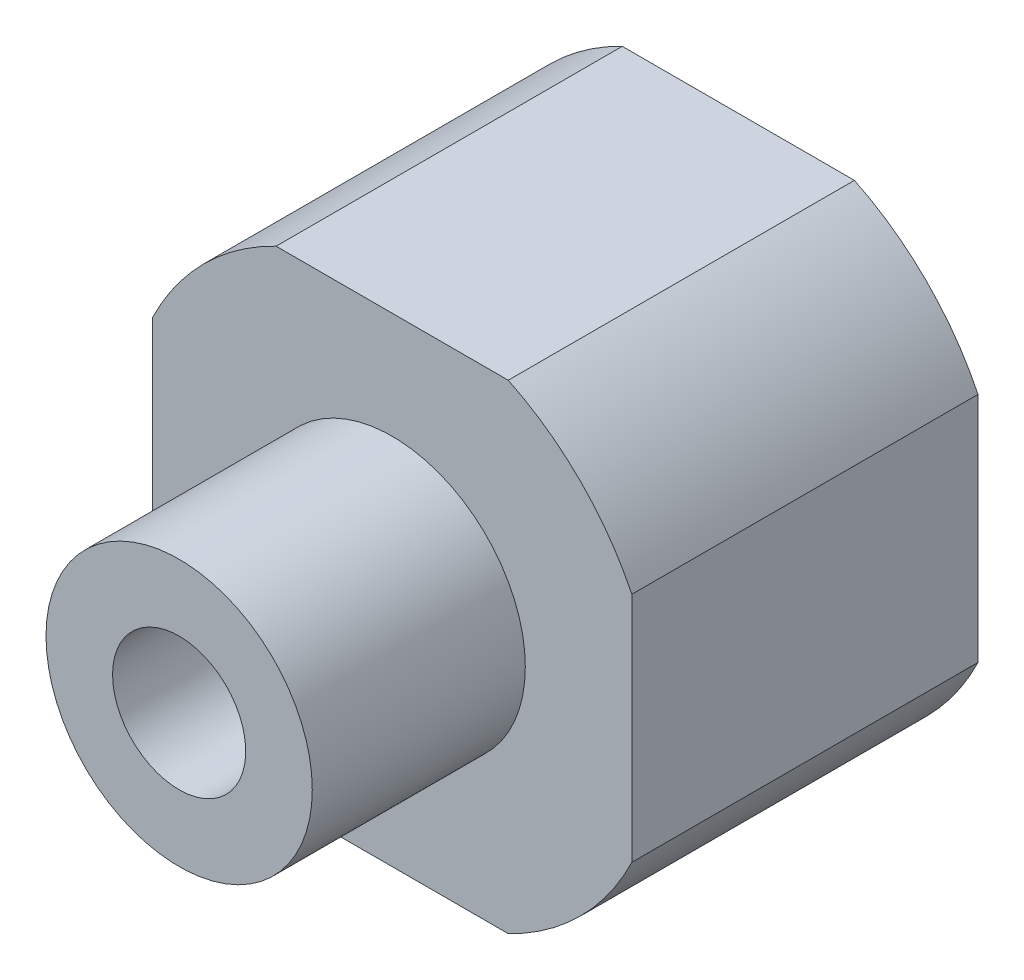
SolidWorks part; units mm, degrees
ref_plane "Front Plane" through (0, 0, 0) normal (0, 0, 1) x (1, 0, 0)
ref_plane "Top Plane" through (0, 0, 0) normal (0, 1, 0) x (1, 0, 0)
ref_plane "Right Plane" through (0, 0, 0) normal (1, 0, 0) x (0, 0, -1)
sketch "Sketch1" plane through (0, 0, 0) normal (0, 0, 1) x (1, 0, 0)
  line L0 (-62.2543, 0) -> (83.1423, 0) construction
  line L1 (0, 58.773) -> (0, -75.9748) construction
  line L3 (-4.3589, 9) -> (4.3589, 9)
  line L4 (-9, 4.3589) -> (-9, -4.3589)
  line L5 (-4.3589, -9) -> (4.3589, -9)
  line L6 (9, 4.3589) -> (9, -4.3589)
  line L7 (-9, 9) -> (9, -9) construction
  line L8 (-9, -9) -> (9, 9) construction
  arc A0 (-4.3589, 9) -> (-9, 4.3589) centre (0, 0) ccw
  arc A1 (9, 4.3589) -> (4.3589, 9) centre (0, 0) ccw
  arc A2 (-9, -4.3589) -> (-4.3589, -9) centre (0, 0) ccw
  arc A3 (4.3589, -9) -> (9, -4.3589) centre (0, 0) ccw
  point P5 (0, 0)
extrude "Boss-Extrude2" add sketch "Sketch1" along normal blind 13
sketch "Sketch2" plane through (0, 0, 0) normal (0, 0, 1) x (1, 0, 0)
  circle A0 centre (0, 0) radius 5
extrude "Boss-Extrude3" add sketch "Sketch2" along normal blind 21
sketch "Sketch4" plane through (0, 0, 0) normal (0, 0, 1) x (1, 0, 0)
  circle A0 centre (0, 0) radius 2.5
extrude "Cut-Extrude1" cut sketch "Sketch4" along normal blind 21
